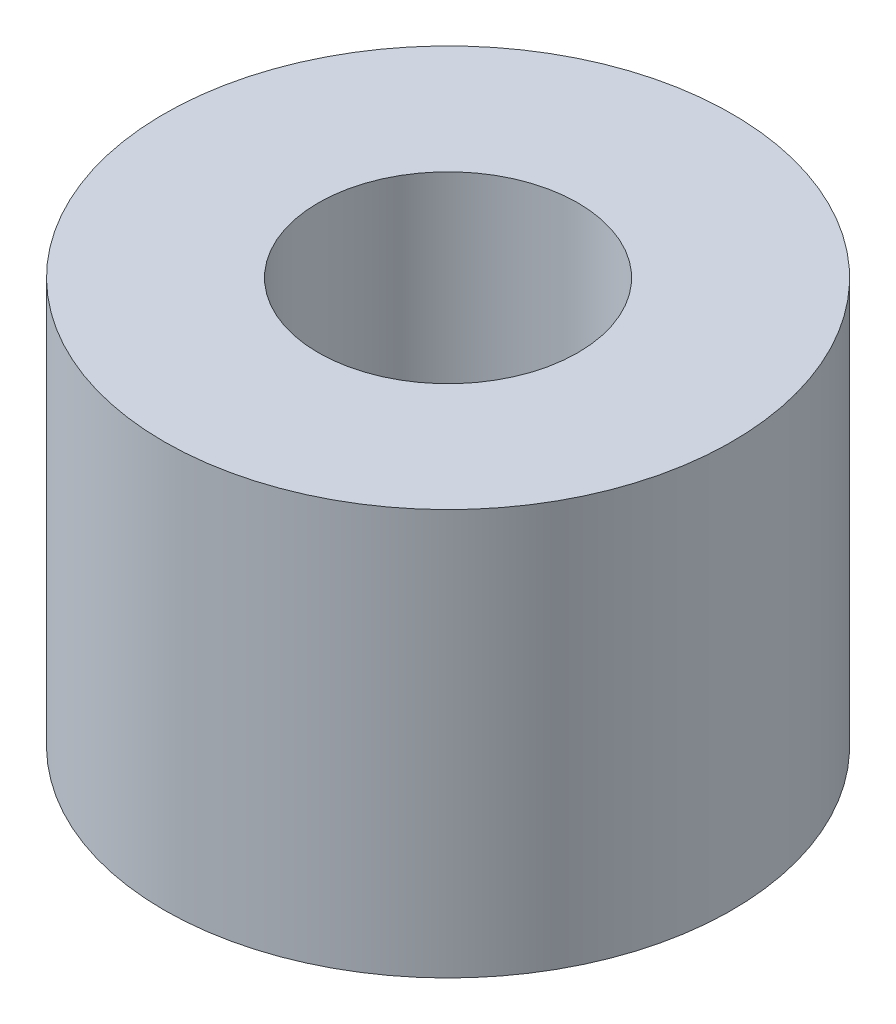
SolidWorks part; units mm, degrees
material "ABS"
ref_plane "Plano frontal" through (0, 0, 0) normal (0, 0, 1) x (1, 0, 0)
ref_plane "Plano superior" through (0, 0, 0) normal (0, 1, 0) x (1, 0, 0)
ref_plane "Plano direito" through (0, 0, 0) normal (1, 0, 0) x (0, 0, -1)
sketch "Esboço1" plane through (0, 0, 0) normal (0, 1, 0) x (1, 0, 0)
  circle A0 centre (0, 0) radius 1.6
  circle A1 centre (0, 0) radius 3.5
  dimension "D1" = 3.2
  dimension "D2" = 7
extrude "Ressalto-extrusão1" add sketch "Esboço1" along normal mid plane 5
